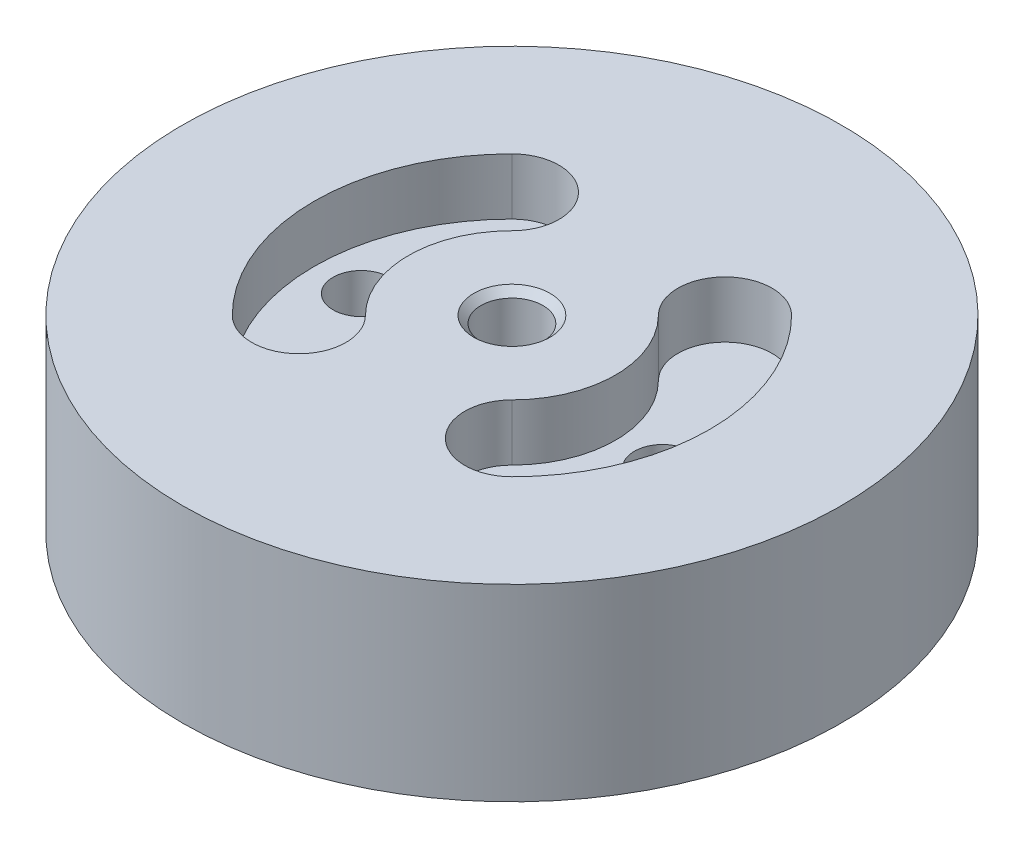
SolidWorks part; units mm, degrees
ref_plane "Ön Düzlem" through (0, 0, 0) normal (0, 0, 1) x (1, 0, 0)
ref_plane "Üst Düzlem" through (0, 0, 0) normal (0, 1, 0) x (1, 0, 0)
ref_plane "Sağ Düzlem" through (0, 0, 0) normal (1, 0, 0) x (0, 0, -1)
sketch "Çizim1" plane through (0, 0, 0) normal (0, 1, 0) x (1, 0, 0)
  circle A0 centre (0, 0) radius 17.5
  dimension "D1" = 35
extrude "Yükseklik-Ekstrüzyon1" add sketch "Çizim1" along normal blind 10
sketch "Çizim2" plane through (0, 10, 0) normal (0, 1, 0) x (1, 0, 0)
  line L0 (-5.6569, 5.6569) -> (0, 0) construction
  line L1 (0, 0) -> (-5.6569, -5.6569) construction
  line L2 (0, -14.6692) -> (0, 14.6692) construction
  circle A0 centre (0, 0) radius 8 construction
  arc A2 (-5.6569, 5.6569) -> (-5.6569, -5.6569) centre (0, 0) ccw construction
  arc A3 (-7.4246, 7.4246) -> (-7.4246, -7.4246) centre (0, 0) ccw
  arc A4 (-3.8891, 3.8891) -> (-3.8891, -3.8891) centre (0, 0) ccw
  arc A5 (-3.8891, 3.8891) -> (-7.4246, 7.4246) centre (-5.6569, 5.6569) ccw
  arc A6 (-7.4246, -7.4246) -> (-3.8891, -3.8891) centre (-5.6569, -5.6569) ccw
  arc A7 (5.6569, 5.6569) -> (5.6569, -5.6569) centre (0, 0) cw construction
  arc A8 (7.4246, 7.4246) -> (7.4246, -7.4246) centre (0, 0) cw
  arc A9 (3.8891, 3.8891) -> (3.8891, -3.8891) centre (0, 0) cw
  arc A10 (3.8891, 3.8891) -> (7.4246, 7.4246) centre (5.6569, 5.6569) cw
  arc A11 (7.4246, -7.4246) -> (3.8891, -3.8891) centre (5.6569, -5.6569) cw
  point P5 (-8, 0)
  point P16 (0, 0)
  point P18 (8, 0)
  dimension "D1" = 16
  dimension "D2" = 2.5
  dimension "D3" = 45
  dimension "D4" = 45
extrude "Kes-Ekstrüzyon1" cut sketch "Çizim2" against normal blind 3 contours A8 A11 A9 A10 | A4 A6 A3 A5
sketch "Çizim3" plane through (0, 0, 0) normal (0, -1, 0) x (1, 0, 0)
  line L0 (0, 0) -> (0, 12.5) construction
  line L1 (0, 0) -> (0, -12.5) construction
  dimension "D1" = 12.5
  dimension "D2" = 12.5
hole_wizard "M4 Dişli Delik1" positions "Çizim4" profile "Çizim5" tap size "M4" standard "ISO"
sketch "Çizim4" plane through (0, 0, 0) normal (0, -1, 0) x (-1, 0, 0)
  point P0 (0, -12.5)
  point P3 (0, 12.5)
sketch "Çizim5" plane through (0, 0, 12.5) normal (1, 0, 0) x (0, 0, -1)
  line L0 (0, 0) -> (0, 8.9914)
  line L1 (0, 8.9914) -> (1.65, 8)
  line L2 (1.65, 8) -> (1.65, 0.375)
  line L3 (1.65, 0.375) -> (2.025, 0)
  line L5 (2.025, 0) -> (0, 0)
  line L6 (-1.65, 0.375) -> (-2.025, 0) construction
  line L10 (0, 8.9914) -> (-1.65, 8) construction
  line L11 (0, -6.35) -> (0, 107.95) construction
  dimension "Tap Drill Dia." = 3.3
  dimension "Tap Drill Depth" = 8
  dimension "Near C'Sink Dia." = 4.05
  dimension "Near C'Sink Angle" = 90
  dimension "Drill Angle" = 118
cosmetic thread "Delik Dişi1" parameters "D1"=8, "D2"=4
cosmetic thread "Delik Dişi2" parameters "D1"=8, "D2"=4
hole_wizard "M4 Dişli Delik2" positions "Çizim8" profile "Çizim9" tap size "M4" standard "ISO" end condition through all
sketch "Çizim8" plane through (0, 10, 0) normal (0, 1, 0) x (1, 0, 0)
  point P0 (0, 0)
sketch "Çizim9" plane through (0, 10, 0) normal (1, 0, 0) x (0, 0, 1)
  line L0 (0, 0) -> (0, 10)
  line L1 (0, 10) -> (1.65, 10)
  line L2 (1.65, 10) -> (1.65, 0.375)
  line L3 (1.65, 0.375) -> (2.025, 0)
  line L5 (2.025, 0) -> (0, 0)
  line L6 (-1.65, 0.375) -> (-2.025, 0) construction
  line L11 (0, -6.35) -> (0, 107.95) construction
  dimension "Thru Tap Drill Dia." = 3.3
  dimension "Thru Tap Drill Depth" = 10
  dimension "Near C'Sink Dia." = 4.05
  dimension "Near C'Sink Angle" = 90
cosmetic thread "Delik Dişi3" parameters "D2"=4
sketch "Çizim10" plane through (0, 7, 0) normal (0, 1, 0) x (1, 0, 0)
  circle A16 centre (0, 0) radius 8 construction
  circle A17 centre (-8, 0) radius 1.5
  circle A18 centre (8, 0) radius 1.5
  point P0 (0, 0)
  dimension "D1" = 16
  dimension "D2" = 3
  dimension "D3" = 3
extrude "Kes-Ekstrüzyon3" cut sketch "Çizim10" against normal through all
